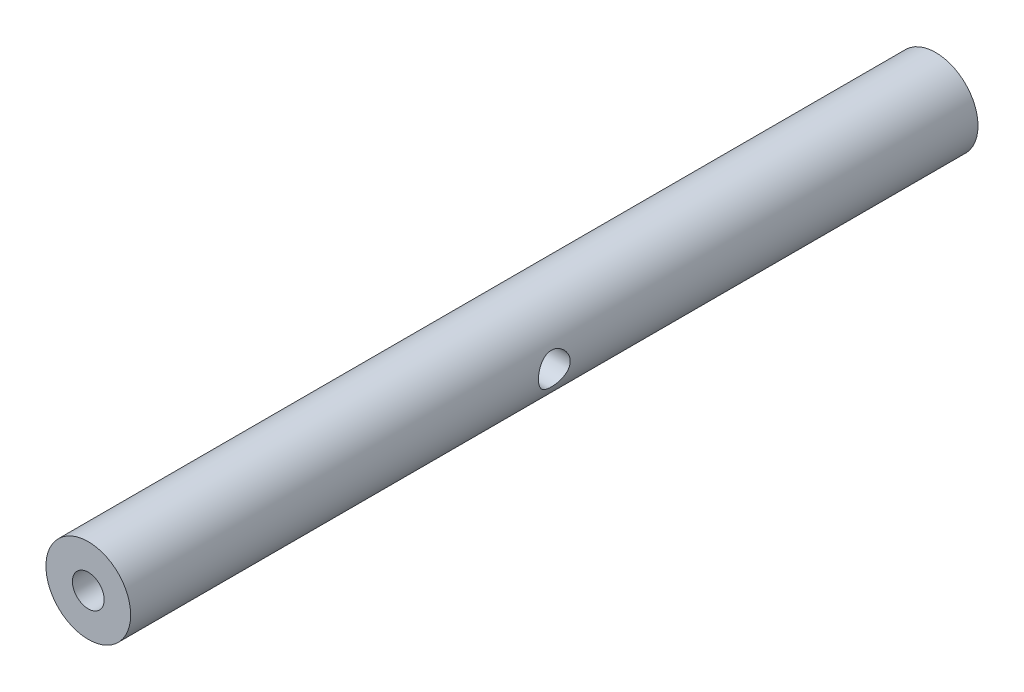
SolidWorks part; units mm, degrees
ref_plane "Plano frontal" through (0, 0, 0) normal (0, 0, 1) x (1, 0, 0)
ref_plane "Plano superior" through (0, 0, 0) normal (0, 1, 0) x (1, 0, 0)
ref_plane "Plano direito" through (0, 0, 0) normal (1, 0, 0) x (0, 0, -1)
sketch "Esboço1" plane through (0, 0, 0) normal (0, 0, 1) x (1, 0, 0)
  circle A0 centre (0, 0) radius 4
  circle A1 centre (0, 0) radius 1.5
extrude "Ressalto-extrusão2" add sketch "Esboço1" along normal blind 80
sketch "Esboço2" plane through (0, 0, 0) normal (1, 0, 0) x (0, 0, -1)
  circle A0 centre (-40, 0) radius 1.5
extrude "Corte-extrusão1" cut sketch "Esboço2" against normal up to next and the other way up to next
